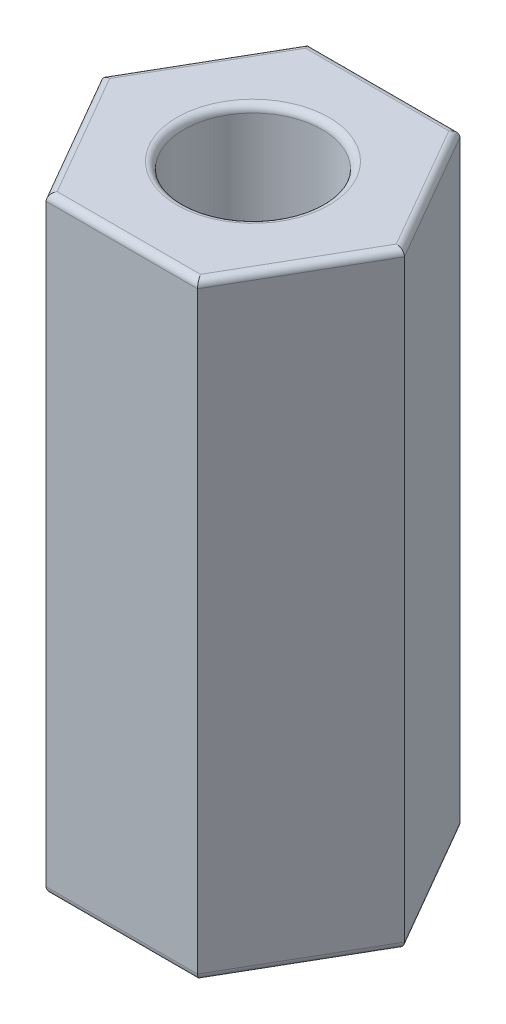
SolidWorks part; units mm, degrees
ref_plane "Front Plane" through (0, 0, 0) normal (0, 0, 1) x (1, 0, 0)
ref_plane "Top Plane" through (0, 0, 0) normal (0, 1, 0) x (1, 0, 0)
ref_plane "Right Plane" through (0, 0, 0) normal (1, 0, 0) x (0, 0, -1)
sketch "Sketch1" plane through (0, 0, 0) normal (0, 1, 0) x (1, 0, 0)
  line L1 (2.7423, 0) -> (1.3711, 2.3749)
  line L2 (1.3711, 2.3749) -> (-1.3711, 2.3749)
  line L3 (-1.3711, 2.3749) -> (-2.7423, 0)
  line L4 (-2.7423, 0) -> (-1.3711, -2.3749)
  line L5 (-1.3711, -2.3749) -> (1.3711, -2.3749)
  line L6 (1.3711, -2.3749) -> (2.7423, 0)
  circle A0 centre (0, 0) radius 2.3749 construction
  dimension "D1" = 4.7498
extrude "Boss-Extrude1" add sketch "Sketch1" along normal mid plane 11
hole_wizard "M3x0.5 Tapped Hole1" positions "Sketch3" profile "Sketch4" tap size "M3x0.5" standard "ANSI Metric" end condition through all
sketch "Sketch3" plane through (0, 5.5, 0) normal (0, 1, 0) x (1, 0, 0)
  point P0 (0, 0)
sketch "Sketch4" plane through (0, 5.5, 0) normal (1, 0, 0) x (0, 0, 1)
  line L0 (0, 0) -> (0, 11)
  line L1 (0, 11) -> (1.25, 11)
  line L2 (1.25, 11) -> (1.25, 0)
  line L5 (1.25, 0) -> (0, 0)
  line L11 (0, -6.35) -> (0, 107.95) construction
  dimension "Thru Tap Drill Dia." = 2.5
  dimension "Thru Tap Drill Depth" = 11
cosmetic thread "Hole Thread1" parameters "D2"=3
fillet "Fillet1" radius 0.127 14 edges at (0, 5.5, 2.3749) (-2.0567, 5.5, 1.1875) (-2.0567, 5.5, -1.1875) (0, 5.5, -2.3749) (2.0567, 5.5, -1.1875) (2.0567, 5.5, 1.1875) (0, 5.5, 1.25) (2.0567, -5.5, -1.1875) (0, -5.5, -2.3749) (-2.0567, -5.5, -1.1875) (-2.0567, -5.5, 1.1875) (0, -5.5, 2.3749) (2.0567, -5.5, 1.1875) (0, -5.5, 1.25)
